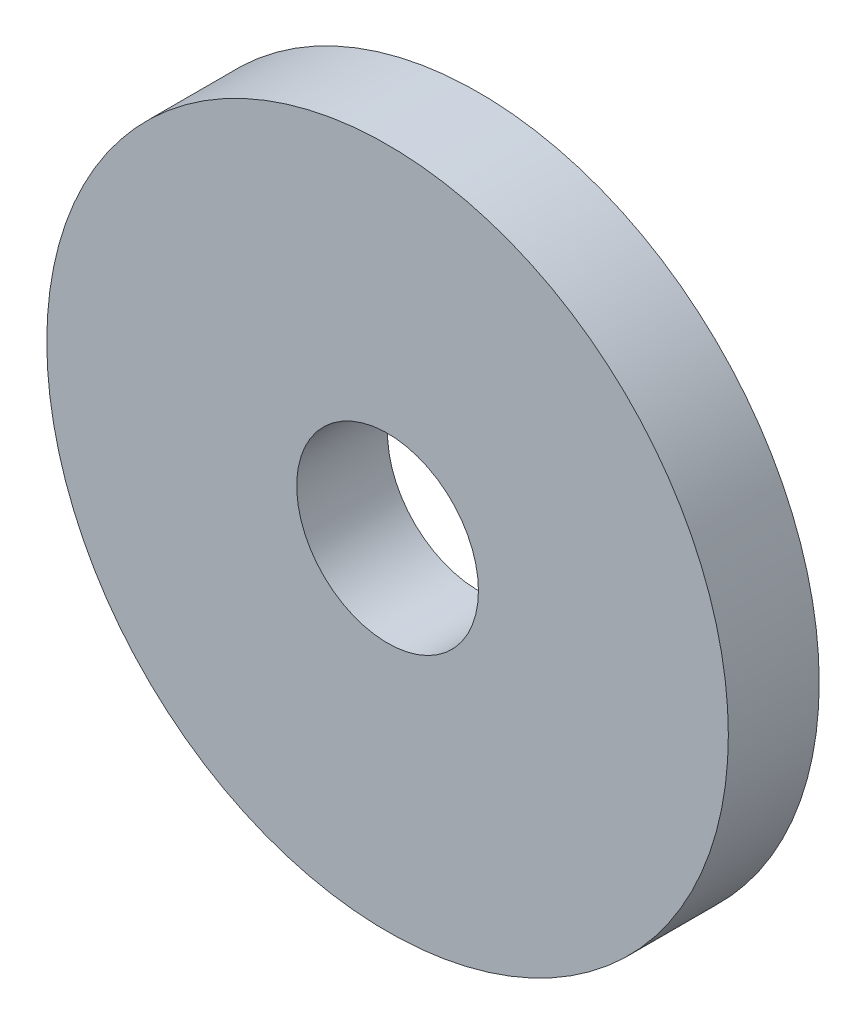
SolidWorks part; units mm, degrees
material "Thornel Mat VMA"
ref_plane "前视基准面" through (0, 0, 0) normal (0, 0, 1) x (1, 0, 0)
ref_plane "上视基准面" through (0, 0, 0) normal (0, 1, 0) x (1, 0, 0)
ref_plane "右视基准面" through (0, 0, 0) normal (1, 0, 0) x (0, 0, -1)
sketch "草图1" plane through (0, 0, 0) normal (0, 0, 1) x (1, 0, 0)
  circle A0 centre (0, 0) radius 7.5
  circle A1 centre (0, 0) radius 2
  dimension "D1" = 15
  dimension "D2" = 4
extrude "凸台-拉伸1" add sketch "草图1" along normal blind 2
